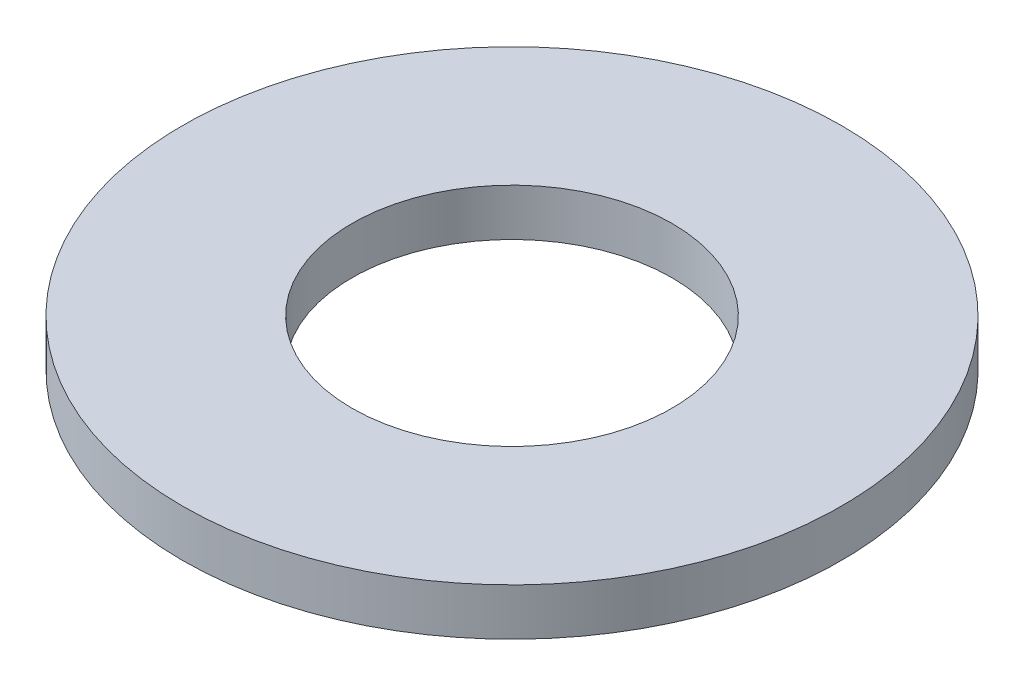
SolidWorks part; units mm, degrees
other "Frame Tie Washer Left"
ref_plane "Front Plane" through (0, 0, 0) normal (0, 0, 1) x (1, 0, 0)
ref_plane "Top Plane" through (0, 0, 0) normal (0, 1, 0) x (1, 0, 0)
ref_plane "Right Plane" through (0, 0, 0) normal (1, 0, 0) x (0, 0, -1)
sketch3d "Base Outline Sketch datum points"
  point P0 (0, 157, 0)
  point P1 (10, 157, 0)
  point P2 (0, 157, -10)
ref_plane "Base Outline Sketch plane" through (0, 157, 0) normal (0, 1, 0) x (1, 0, 0)
sketch "Base Outline Sketch" plane through (0, 157, 0) normal (0, 1, 0) x (1, 0, 0)
  circle A0 centre (-56.2917, -50) radius 3.5
  circle A1 centre (-56.2917, -50) radius 1.7
extrude "Base Outline" add sketch "Base Outline Sketch" along normal blind 0.5 separate body
